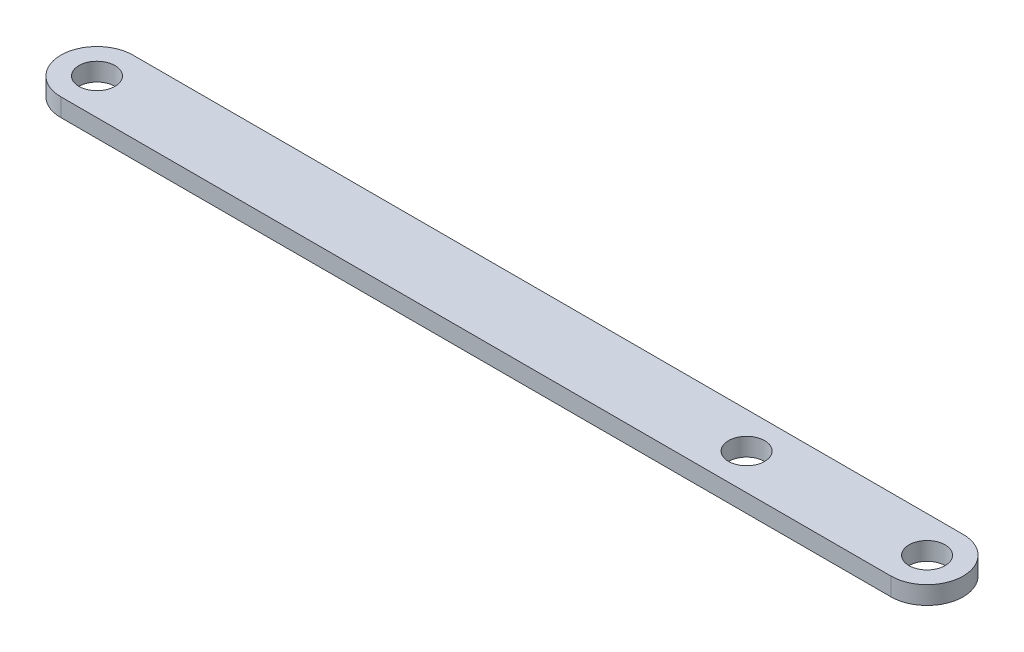
SolidWorks part; units mm, degrees
ref_plane "Front Plane" through (0, 0, 0) normal (0, 0, 1) x (1, 0, 0)
ref_plane "Top Plane" through (0, 0, 0) normal (0, 1, 0) x (1, 0, 0)
ref_plane "Right Plane" through (0, 0, 0) normal (1, 0, 0) x (0, 0, -1)
sketch "Sketch1" plane through (0, 0, 0) normal (0, 1, 0) x (1, 0, 0)
  line L0 (-72.3468, 0) -> (157.6532, 0) construction
  line L1 (-72.3468, 10) -> (157.6532, 10)
  line L2 (-72.3468, -10) -> (157.6532, -10)
  arc A0 (-72.3468, 10) -> (-72.3468, -10) centre (-72.3468, 0) ccw
  arc A1 (157.6532, -10) -> (157.6532, 10) centre (157.6532, 0) ccw
  circle A2 centre (-72.3468, 0) radius 5
  circle A3 centre (157.6532, 0) radius 5
  point P3 (42.6532, 0)
  dimension "D1" = 230
  dimension "D2" = 10
  dimension "D3" = 10
  dimension "D4" = 10
extrude "Boss-Extrude1" add sketch "Sketch1" along normal blind 5
sketch "Sketch2" plane through (0, 5, 0) normal (0, 1, 0) x (1, 0, 0)
  circle A0 centre (107.6532, 0) radius 5
  arc A2 (157.6532, -10) -> (157.6532, 10) centre (157.6532, 0) ccw construction
  dimension "D1" = 10
  dimension "D2" = 50
extrude "Cut-Extrude1" cut sketch "Sketch2" against normal blind 10
